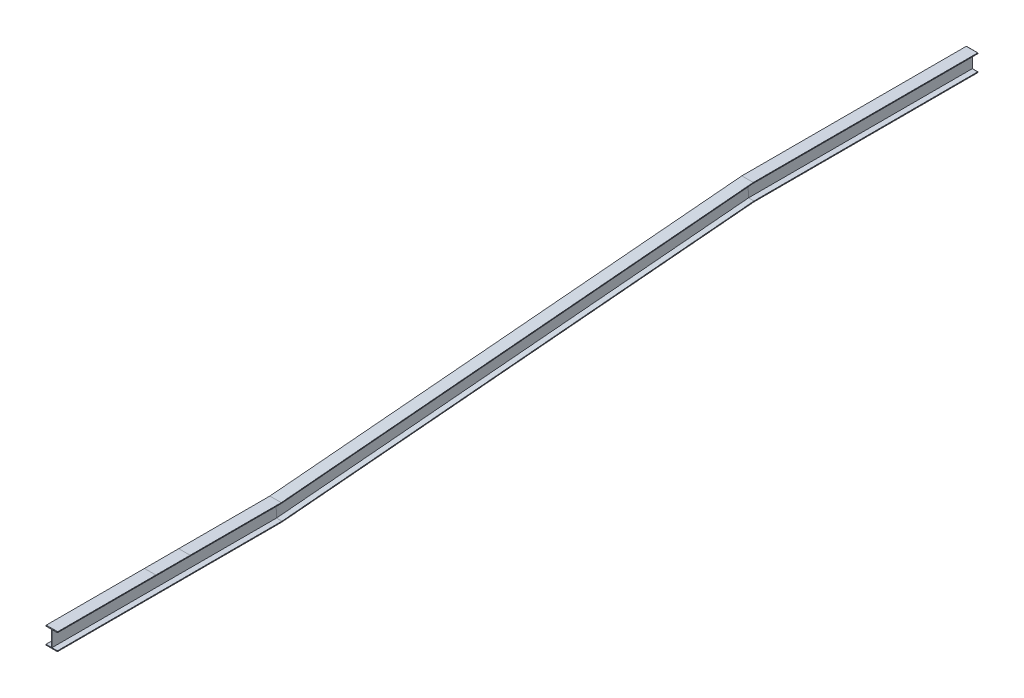
SolidWorks part; units mm, degrees
material "ASTM A992 Steel"
ref_plane "Front" through (0, 0, 0) normal (0, 0, 1) x (1, 0, 0)
ref_plane "Top" through (0, 0, 0) normal (0, 1, 0) x (1, 0, 0)
ref_plane "Right" through (0, 0, 0) normal (1, 0, 0) x (0, 0, -1)
sketch "Sketch1" plane through (0, 0, 0) normal (0, 0, 1) x (1, 0, 0)
  line L0 (0, -0.0002) -> (101.6, -0.0002)
  line L1 (101.6, -0.0002) -> (101.6, -7.1122)
  line L2 (101.6, -7.1122) -> (53.408, -7.1122)
  line L3 (53.408, -7.1122) -> (53.408, -146.0502)
  line L4 (53.408, -146.0502) -> (101.6, -146.0502)
  line L5 (101.6, -146.0502) -> (101.6, -153.1622)
  line L6 (101.6, -153.1622) -> (0, -153.1622)
  line L7 (0, -153.1622) -> (0, -146.0502)
  line L8 (0, -146.0502) -> (47.566, -146.0502)
  line L9 (47.566, -146.0502) -> (47.566, -7.1122)
  line L10 (47.566, -7.1122) -> (0, -7.1122)
  line L11 (0, -7.1122) -> (0, -0.0002)
  line L12 (50.8, -0.0002) -> (50.8, -153.1622) construction
  point P15 (50.8, -76.5812)
  dimension "D1" = 5.842
  dimension "D2" = 7.112
  dimension "D3" = 7.112
  dimension "D4" = 7.112
  dimension "D5" = 153.162
  dimension "D6" = 50.8
  dimension "D7" = 50.8
  dimension "D8" = 47.566
sketch "Sketch2" plane through (0, 0, 0) normal (1, 0, 0) x (0, 0, -1)
  line L0 (0, -76.5812) -> (1930, -76.5812)
  line L1 (1930, -76.5812) -> (6128.7777, 290.7642)
  line L2 (6128.7777, 290.7642) -> (8058.7777, 290.7642)
  line L3 (1930, -76.5812) -> (909.297, -76.5812) construction
  dimension "D1" = 5
  dimension "D2" = 1930
  dimension "D3" = 4214.8163
  dimension "D4" = 1930
sweep "Sweep1" add profiles "Sketch1" path "Sketch2"
sketch "Sketch3" plane through (0, -0.0002, 0) normal (0, 1, 0) x (1, 0, 0)
  line L0 (101.6, 0) -> (101.6, 1926.6564) construction
  line L1 (101.6, 963.3282) -> (101.6, 810.9282)
  line L2 (101.6, 810.9282) -> (0, 810.9282)
  line L3 (0, 0) -> (0, 1926.6564) construction
  line L4 (0, 810.9282) -> (0, 963.3282)
  line L5 (0, 963.3282) -> (0, 1115.7282)
  line L6 (0, 1115.7282) -> (101.6, 1115.7282)
  line L7 (101.6, 1115.7282) -> (101.6, 963.3282)
  point P0 (101.6, 963.3282)
  dimension "D1" = 152.4
  dimension "D2" = 152.4
split line "Split Line1"
sketch "Sketch4" plane through (0, 0, -8058.7777) normal (0, 0, -1) x (-1, 0, 0)
  line L12 (0, 360.2332) -> (0, 367.3452)
  line L13 (0, 367.3452) -> (-101.6, 367.3452)
  line L14 (-101.6, 367.3452) -> (-101.6, 360.2332)
  line L15 (-101.6, 360.2332) -> (-53.408, 360.2332)
  line L16 (-53.408, 360.2332) -> (-53.408, 221.2952)
  line L17 (-53.408, 221.2952) -> (-101.6, 221.2952)
  line L18 (-101.6, 221.2952) -> (-101.6, 214.1832)
  line L19 (-101.6, 214.1832) -> (0, 214.1832)
  line L20 (0, 214.1832) -> (0, 221.2952)
  line L21 (0, 221.2952) -> (-47.566, 221.2952)
  line L22 (-47.566, 221.2952) -> (-47.566, 360.2332)
  line L23 (-47.566, 360.2332) -> (0, 360.2332)
  line L24 (0, 360.2332) -> (0, 367.3452)
  line L25 (0, 367.3452) -> (-101.6, 367.3452)
  line L26 (-101.6, 367.3452) -> (-101.6, 360.2332)
  line L27 (-101.6, 360.2332) -> (-53.408, 360.2332)
  line L28 (-53.408, 360.2332) -> (-53.408, 221.2952)
  line L29 (-53.408, 221.2952) -> (-101.6, 221.2952)
  line L30 (-101.6, 221.2952) -> (-101.6, 214.1832)
  line L31 (-101.6, 214.1832) -> (0, 214.1832)
  line L32 (0, 214.1832) -> (0, 221.2952)
  line L33 (0, 221.2952) -> (-47.566, 221.2952)
  line L34 (-47.566, 221.2952) -> (-47.566, 360.2332)
  line L35 (-47.566, 360.2332) -> (0, 360.2332)
  dimension "D1" = 0
extrude "Boss-Extrude1" add sketch "Sketch4" along normal up to surface (14.5416 mm away)
sketch "Sketch5" plane through (0, 0, 0) normal (0, 0, 1) x (1, 0, 0)
  line L12 (0, -0.0002) -> (0, -7.1122)
  line L13 (0, -7.1122) -> (47.566, -7.1122)
  line L14 (47.566, -7.1122) -> (47.566, -146.0502)
  line L15 (47.566, -146.0502) -> (0, -146.0502)
  line L16 (0, -146.0502) -> (0, -153.1622)
  line L17 (0, -153.1622) -> (101.6, -153.1622)
  line L18 (101.6, -153.1622) -> (101.6, -146.0502)
  line L19 (101.6, -146.0502) -> (53.408, -146.0502)
  line L20 (53.408, -146.0502) -> (53.408, -7.1122)
  line L21 (53.408, -7.1122) -> (101.6, -7.1122)
  line L22 (101.6, -7.1122) -> (101.6, -0.0002)
  line L23 (101.6, -0.0002) -> (0, -0.0002)
  line L24 (0, -0.0002) -> (0, -7.1122)
  line L25 (0, -7.1122) -> (47.566, -7.1122)
  line L26 (47.566, -7.1122) -> (47.566, -146.0502)
  line L27 (47.566, -146.0502) -> (0, -146.0502)
  line L28 (0, -146.0502) -> (0, -153.1622)
  line L29 (0, -153.1622) -> (101.6, -153.1622)
  line L30 (101.6, -153.1622) -> (101.6, -146.0502)
  line L31 (101.6, -146.0502) -> (53.408, -146.0502)
  line L32 (53.408, -146.0502) -> (53.408, -7.1122)
  line L33 (53.408, -7.1122) -> (101.6, -7.1122)
  line L34 (101.6, -7.1122) -> (101.6, -0.0002)
  line L35 (101.6, -0.0002) -> (0, -0.0002)
  dimension "D1" = 0
extrude "Boss-Extrude2" add sketch "Sketch5" along normal up to surface (11.1092 mm away)
sketch "Sketch6" plane through (0, 0, -8073.3193) normal (0, 0, -1) x (-1, 0, 0)
  line L12 (-47.566, 221.2952) -> (-47.566, 360.2332)
  line L13 (-47.566, 360.2332) -> (0, 360.2332)
  line L14 (0, 360.2332) -> (0, 367.3452)
  line L15 (0, 367.3452) -> (-101.6, 367.3452)
  line L16 (-101.6, 367.3452) -> (-101.6, 360.2332)
  line L17 (-101.6, 360.2332) -> (-53.408, 360.2332)
  line L18 (-53.408, 360.2332) -> (-53.408, 221.2952)
  line L19 (-53.408, 221.2952) -> (-101.6, 221.2952)
  line L20 (-101.6, 221.2952) -> (-101.6, 214.1832)
  line L21 (-101.6, 214.1832) -> (0, 214.1832)
  line L22 (0, 214.1832) -> (0, 221.2952)
  line L23 (0, 221.2952) -> (-47.566, 221.2952)
  line L24 (-47.566, 221.2952) -> (-47.566, 360.2332)
  line L25 (-47.566, 360.2332) -> (0, 360.2332)
  line L26 (0, 360.2332) -> (0, 367.3452)
  line L27 (0, 367.3452) -> (-101.6, 367.3452)
  line L28 (-101.6, 367.3452) -> (-101.6, 360.2332)
  line L29 (-101.6, 360.2332) -> (-53.408, 360.2332)
  line L30 (-53.408, 360.2332) -> (-53.408, 221.2952)
  line L31 (-53.408, 221.2952) -> (-101.6, 221.2952)
  line L32 (-101.6, 221.2952) -> (-101.6, 214.1832)
  line L33 (-101.6, 214.1832) -> (0, 214.1832)
  line L34 (0, 214.1832) -> (0, 221.2952)
  line L35 (0, 221.2952) -> (-47.566, 221.2952)
  dimension "D1" = 0
extrude "Boss-Extrude4" [suppressed] add sketch "Sketch6" along normal up to surface (73.152 mm away)
fillet "Fillet1" [suppressed] radius 22.7686
sketch "Sketch7" plane through (0, 0, 11.1092) normal (0, 0, 1) x (1, 0, 0)
  line L12 (101.6, -7.1122) -> (101.6, -0.0002)
  line L13 (101.6, -0.0002) -> (0, -0.0002)
  line L14 (0, -0.0002) -> (0, -7.1122)
  line L15 (0, -7.1122) -> (47.566, -7.1122)
  line L16 (47.566, -7.1122) -> (47.566, -146.0502)
  line L17 (47.566, -146.0502) -> (0, -146.0502)
  line L18 (0, -146.0502) -> (0, -153.1622)
  line L19 (0, -153.1622) -> (101.6, -153.1622)
  line L20 (101.6, -153.1622) -> (101.6, -146.0502)
  line L21 (101.6, -146.0502) -> (53.408, -146.0502)
  line L22 (53.408, -146.0502) -> (53.408, -7.1122)
  line L23 (53.408, -7.1122) -> (101.6, -7.1122)
  line L24 (101.6, -7.1122) -> (101.6, -0.0002)
  line L25 (101.6, -0.0002) -> (0, -0.0002)
  line L26 (0, -0.0002) -> (0, -7.1122)
  line L27 (0, -7.1122) -> (47.566, -7.1122)
  line L28 (47.566, -7.1122) -> (47.566, -146.0502)
  line L29 (47.566, -146.0502) -> (0, -146.0502)
  line L30 (0, -146.0502) -> (0, -153.1622)
  line L31 (0, -153.1622) -> (101.6, -153.1622)
  line L32 (101.6, -153.1622) -> (101.6, -146.0502)
  line L33 (101.6, -146.0502) -> (53.408, -146.0502)
  line L34 (53.408, -146.0502) -> (53.408, -7.1122)
  line L35 (53.408, -7.1122) -> (101.6, -7.1122)
  dimension "D1" = 0
extrude "Boss-Extrude5" add sketch "Sketch7" along normal up to surface (53.8654 mm away)
sketch "Sketch8" plane through (0, 0, -8073.3193) normal (0, 0, -1) x (-1, 0, 0)
  line L12 (-47.566, 221.2952) -> (-47.566, 360.2332)
  line L13 (-47.566, 360.2332) -> (0, 360.2332)
  line L14 (0, 360.2332) -> (0, 367.3452)
  line L15 (0, 367.3452) -> (-101.6, 367.3452)
  line L16 (-101.6, 367.3452) -> (-101.6, 360.2332)
  line L17 (-101.6, 360.2332) -> (-53.408, 360.2332)
  line L18 (-53.408, 360.2332) -> (-53.408, 221.2952)
  line L19 (-53.408, 221.2952) -> (-101.6, 221.2952)
  line L20 (-101.6, 221.2952) -> (-101.6, 214.1832)
  line L21 (-101.6, 214.1832) -> (0, 214.1832)
  line L22 (0, 214.1832) -> (0, 221.2952)
  line L23 (0, 221.2952) -> (-47.566, 221.2952)
  line L24 (-47.566, 221.2952) -> (-47.566, 360.2332)
  line L25 (-47.566, 360.2332) -> (0, 360.2332)
  line L26 (0, 360.2332) -> (0, 367.3452)
  line L27 (0, 367.3452) -> (-101.6, 367.3452)
  line L28 (-101.6, 367.3452) -> (-101.6, 360.2332)
  line L29 (-101.6, 360.2332) -> (-53.408, 360.2332)
  line L30 (-53.408, 360.2332) -> (-53.408, 221.2952)
  line L31 (-53.408, 221.2952) -> (-101.6, 221.2952)
  line L32 (-101.6, 221.2952) -> (-101.6, 214.1832)
  line L33 (-101.6, 214.1832) -> (0, 214.1832)
  line L34 (0, 214.1832) -> (0, 221.2952)
  line L35 (0, 221.2952) -> (-47.566, 221.2952)
  dimension "D1" = 0
extrude "Boss-Extrude6" add sketch "Sketch8" along normal up to surface (51.7901 mm away)
fillet "Fillet2" radius 3.175 2 edges at (50.8, -0.0002, 64.9746) (50.8, 367.3452, -8125.1094)
sketch "Sketch9" plane through (0, 214.1832, 0) normal (0, -1, 0) x (1, 0, 0)
  line L4 (101.6, -6132.1213) -> (0, -6132.1213)
  line L5 (0, -6132.1213) -> (0, -8125.1094)
  line L6 (0, -8125.1094) -> (101.6, -8125.1094)
  line L7 (101.6, -8125.1094) -> (101.6, -6132.1213)
  line L8 (101.6, -6132.1213) -> (0, -6132.1213)
  line L9 (0, -6132.1213) -> (0, -8125.1094)
  line L10 (0, -8125.1094) -> (101.6, -8125.1094)
  line L11 (101.6, -8125.1094) -> (101.6, -6132.1213)
  dimension "D1" = 0
extrude "Boss-Extrude7" add sketch "Sketch9" along normal up to surface (0.1882 mm away)
fillet "Fillet3" radius 3.175 2 edges at (77.504, 221.2952, -8125.1094) (23.783, 221.2952, -8125.1094)
